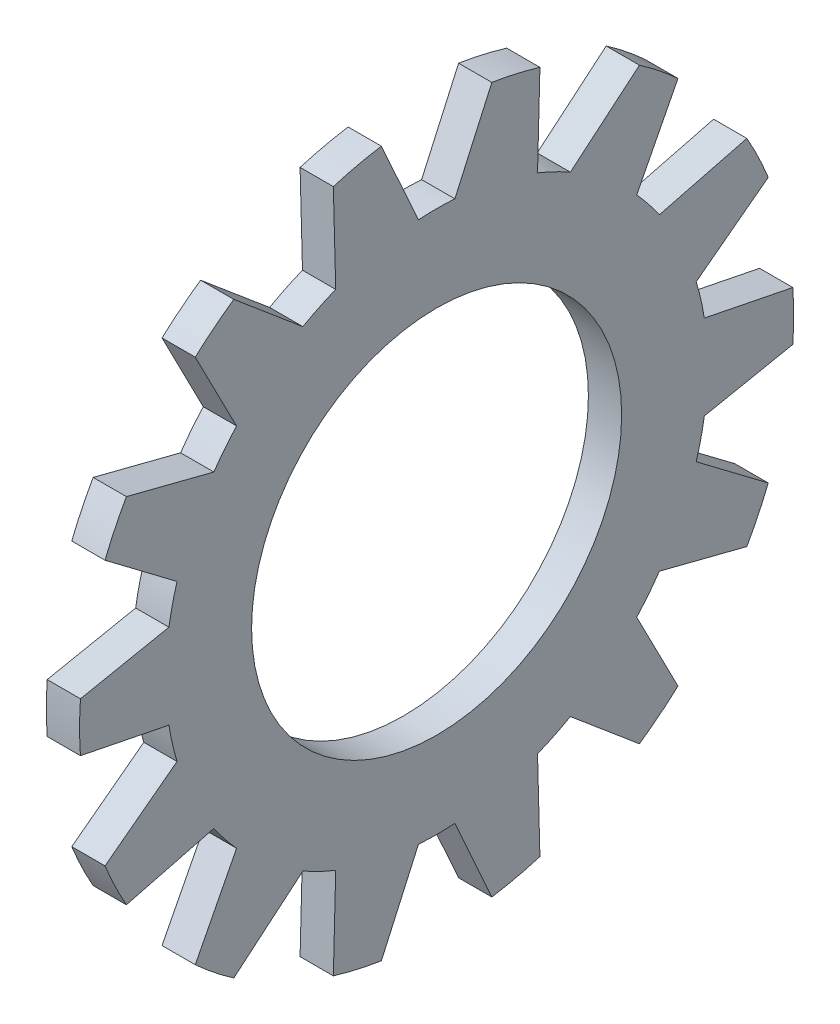
SolidWorks part; units mm, degrees
ref_plane "Plane1" through (0, 0, 0) normal (0, 0, 1) x (1, 0, 0)
ref_plane "Plane2" through (0, 0, 0) normal (0, 1, 0) x (1, 0, 0)
ref_plane "Plane3" through (0, 0, 0) normal (1, 0, 0) x (0, 0, -1)
sketch "SecSke" plane through (0, 0, 0) normal (0, 0, 1) x (1, 0, 0)
  line L0 (-34.925, 0) -> (9.525, 0) construction
  line L1 (0, 3.2512) -> (0, 6.2738)
  line L2 (0, 6.2738) -> (-0.5842, 6.2738)
  line L3 (-0.5842, 6.2738) -> (-0.5842, 3.2512)
  line L4 (-0.5842, 3.2512) -> (0, 3.2512)
  dimension "Thickness" = 0.5842
revolve "Body" add sketch "SecSke" angle 360 about L0
sketch "ExtCutSke" plane through (0, 0, 0) normal (1, 0, 0) x (0, 0, -1)
  line L0 (0, 0) -> (0, 6.5875) construction
  line L1 (-1.1034, 6.4944) -> (-0.3204, 4.7517)
  line L2 (1.1034, 6.4944) -> (0.3204, 4.7517)
  arc A0 (1.1034, 6.4944) -> (-1.1034, 6.4944) centre (0, 0) ccw
  arc A1 (0.3204, 4.7517) -> (-0.3204, 4.7517) centre (0, 0) ccw
  dimension "Cut_dia" = 7.493
  dimension "Clr_dia" = 10.5347
  dimension "Cut_ang" = 7.714
  dimension "Clr_ang" = 19.286
extrude "ExtCut" cut sketch "ExtCutSke" against normal through all
pattern_circular "ExtCuts" count 14 every 25.714 about axis through (-34.925, 0, 0) along (1, 0, 0) of "ExtCut"
equation "' \"Inside_dia@SecSke\" = 16"
equation "' \"Outside_dia@SecSke\" = 26"
equation "' \"Thickness@SecSke\" = 1.2"
equation "' \"Count@ExtCuts\" = 14"
equation "' \"Inside_dia@SecSke\" = 10.5"
equation "' \"Outside_dia@SecSke\" = 18"
equation "' \"Thickness@SecSke\" = 0.9"
equation "' \"Count@ExtCuts\" = 12"
equation "' \"Inside_dia@SecSke\" = 6.4"
equation "' \"Outside_dia@SecSke\" = 11"
equation "' \"Thickness@SecSke\" = 0.6"
equation "' \"Inside_dia@SecSke\" = 4.3"
equation "' \"Outside_dia@SecSke\" = 8.5"
equation "' \"Thickness@SecSke\" = 0.45"
equation "' \"Count@ExtCuts\" = 9"
equation "\"Angle@ExtCuts\" = 360 / \"Count@ExtCuts\""
equation "\"Clr_dia@ExtCutSke\" =  \"Outside_dia@SecSke\" * 1.05"
equation "\"Cut_dia@ExtCutSke\" = \"Outside_dia@SecSke\" - (\"Outside_dia@SecSke\"  - \"Inside_dia@SecSke\" ) * 0.5"
equation "\"Clr_ang@ExtCutSke\" = (360 / \"Count@ExtCuts\") * 0.75"
equation "\"Cut_ang@ExtCutSke\" = (360 / \"Count@ExtCuts\") * 0.3"
